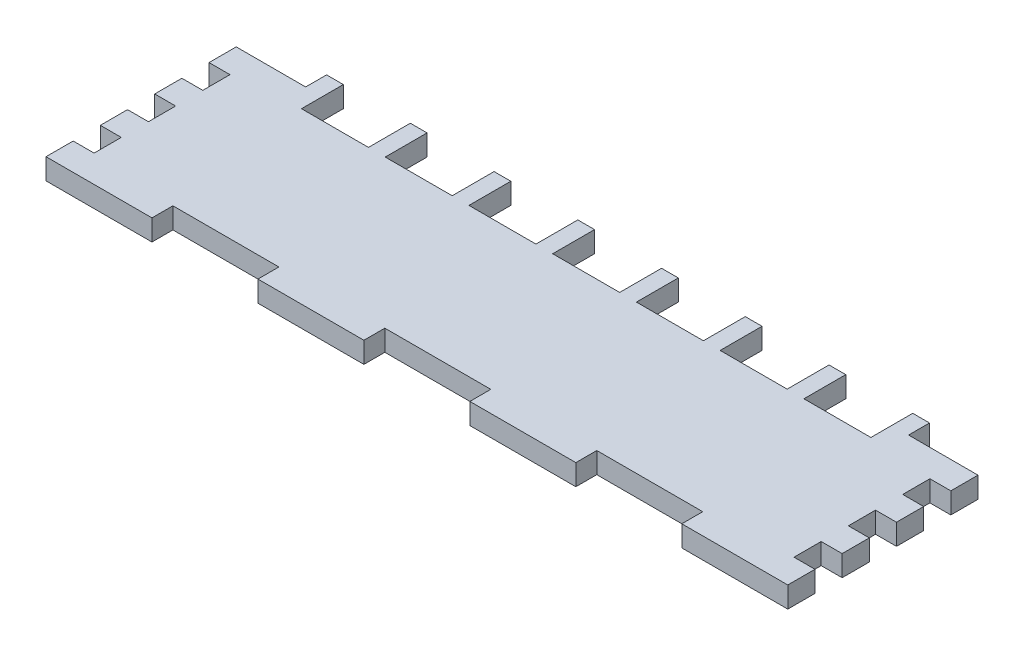
SolidWorks part; units mm, degrees
ref_plane "Front Plane" through (0, 0, 0) normal (0, 0, 1) x (1, 0, 0)
ref_plane "Top Plane" through (0, 0, 0) normal (0, 1, 0) x (1, 0, 0)
ref_plane "Right Plane" through (0, 0, 0) normal (1, 0, 0) x (0, 0, -1)
sketch "Sketch1" plane through (0, 0, 0) normal (0, 1, 0) x (1, 0, 0)
  line L48 (32.1429, 0) -> (32.1429, 6.35)
  line L49 (0, 0) -> (32.1429, 0)
  line L50 (0, 0) -> (0, 6.35)
  line L51 (0, 6.35) -> (32.1429, 6.35)
  line L52 (32.1429, 0) -> (32.1429, 6.35)
  line L53 (0, 0) -> (6.35, 0)
  line L54 (0, 0) -> (0, 8.2429)
  line L55 (0, 8.2429) -> (6.35, 8.2429)
  line L56 (6.35, 0) -> (6.35, 8.2429)
  line L57 (32.1429, 0) -> (64.2857, 0)
  line L58 (64.2857, 0) -> (64.2857, 6.35)
  line L59 (32.1429, 6.35) -> (64.2857, 6.35)
  line L60 (64.2857, 0) -> (64.2857, 6.35)
  line L61 (64.2857, 0) -> (96.4286, 0)
  line L62 (96.4286, 0) -> (96.4286, 6.35)
  line L63 (64.2857, 6.35) -> (96.4286, 6.35)
  line L64 (96.4286, 0) -> (96.4286, 6.35)
  line L65 (96.4286, 0) -> (128.5714, 0)
  line L66 (128.5714, 0) -> (128.5714, 6.35)
  line L67 (96.4286, 6.35) -> (128.5714, 6.35)
  line L72 (128.5714, 0) -> (128.5714, 6.35)
  line L73 (128.5714, 0) -> (160.7143, 0)
  line L74 (160.7143, 0) -> (160.7143, 6.35)
  line L75 (128.5714, 6.35) -> (160.7143, 6.35)
  line L76 (160.7143, 0) -> (160.7143, 6.35)
  line L77 (160.7143, 0) -> (192.8571, 0)
  line L78 (192.8571, 0) -> (192.8571, 6.35)
  line L79 (160.7143, 6.35) -> (192.8571, 6.35)
  line L80 (192.8571, 0) -> (192.8571, 6.35)
  line L81 (192.8571, 0) -> (225, 0)
  line L82 (225, 0) -> (225, 6.35)
  line L83 (192.8571, 6.35) -> (225, 6.35)
  line L84 (0, 8.2429) -> (0, 16.4857)
  line L85 (0, 8.2429) -> (6.35, 8.2429)
  line L86 (6.35, 8.2429) -> (6.35, 16.4857)
  line L87 (0, 16.4857) -> (6.35, 16.4857)
  line L88 (0, 16.4857) -> (0, 24.7286)
  line L89 (0, 16.4857) -> (6.35, 16.4857)
  line L90 (6.35, 16.4857) -> (6.35, 24.7286)
  line L91 (0, 24.7286) -> (6.35, 24.7286)
  line L98 (0, 24.7286) -> (0, 32.9714)
  line L99 (0, 24.7286) -> (6.35, 24.7286)
  line L100 (6.35, 24.7286) -> (6.35, 32.9714)
  line L101 (0, 32.9714) -> (6.35, 32.9714)
  line L102 (0, 32.9714) -> (0, 41.2143)
  line L103 (0, 32.9714) -> (6.35, 32.9714)
  line L104 (6.35, 32.9714) -> (6.35, 41.2143)
  line L105 (0, 41.2143) -> (6.35, 41.2143)
  line L106 (0, 41.2143) -> (0, 49.4571)
  line L107 (0, 41.2143) -> (6.35, 41.2143)
  line L108 (6.35, 41.2143) -> (6.35, 49.4571)
  line L109 (0, 49.4571) -> (6.35, 49.4571)
  line L110 (0, 49.4571) -> (0, 57.7)
  line L111 (0, 49.4571) -> (6.35, 49.4571)
  line L112 (6.35, 49.4571) -> (6.35, 57.7)
  line L113 (0, 57.7) -> (6.35, 57.7)
  line L114 (112.5, 0) -> (112.5, 671.069) construction
  line L115 (-187.856, 28.85) -> (254.8092, 28.85) construction
  line L116 (225, 8.2429) -> (218.65, 8.2429)
  line L117 (218.65, 0) -> (218.65, 8.2429)
  line L118 (225, 0) -> (218.65, 0)
  line L119 (225, 0) -> (225, 8.2429)
  line L120 (225, 49.4571) -> (218.65, 49.4571)
  line L121 (218.65, 49.4571) -> (218.65, 57.7)
  line L122 (225, 57.7) -> (218.65, 57.7)
  line L123 (225, 49.4571) -> (225, 57.7)
  line L124 (225, 41.2143) -> (218.65, 41.2143)
  line L125 (218.65, 41.2143) -> (218.65, 49.4571)
  line L126 (225, 49.4571) -> (218.65, 49.4571)
  line L127 (225, 41.2143) -> (225, 49.4571)
  line L128 (225, 8.2429) -> (218.65, 8.2429)
  line L129 (218.65, 8.2429) -> (218.65, 16.4857)
  line L130 (225, 16.4857) -> (218.65, 16.4857)
  line L131 (225, 8.2429) -> (225, 16.4857)
  line L132 (225, 32.9714) -> (218.65, 32.9714)
  line L133 (218.65, 32.9714) -> (218.65, 41.2143)
  line L134 (225, 41.2143) -> (218.65, 41.2143)
  line L135 (225, 32.9714) -> (225, 41.2143)
  line L136 (225, 24.7286) -> (218.65, 24.7286)
  line L137 (218.65, 24.7286) -> (218.65, 32.9714)
  line L138 (225, 32.9714) -> (218.65, 32.9714)
  line L139 (225, 24.7286) -> (225, 32.9714)
  line L140 (225, 16.4857) -> (218.65, 16.4857)
  line L141 (218.65, 16.4857) -> (218.65, 24.7286)
  line L142 (225, 24.7286) -> (218.65, 24.7286)
  line L143 (225, 16.4857) -> (225, 24.7286)
  line L144 (192.8571, 57.7) -> (225, 57.7)
  line L145 (225, 57.7) -> (225, 51.35)
  line L146 (192.8571, 51.35) -> (225, 51.35)
  line L147 (192.8571, 57.7) -> (192.8571, 51.35)
  line L148 (160.7143, 57.7) -> (192.8571, 57.7)
  line L149 (192.8571, 57.7) -> (192.8571, 51.35)
  line L150 (160.7143, 51.35) -> (192.8571, 51.35)
  line L151 (160.7143, 57.7) -> (160.7143, 51.35)
  line L152 (128.5714, 57.7) -> (160.7143, 57.7)
  line L153 (160.7143, 57.7) -> (160.7143, 51.35)
  line L154 (128.5714, 51.35) -> (160.7143, 51.35)
  line L155 (128.5714, 57.7) -> (128.5714, 51.35)
  line L156 (96.4286, 57.7) -> (128.5714, 57.7)
  line L157 (128.5714, 57.7) -> (128.5714, 51.35)
  line L158 (96.4286, 51.35) -> (128.5714, 51.35)
  line L159 (96.4286, 57.7) -> (96.4286, 51.35)
  line L160 (64.2857, 57.7) -> (96.4286, 57.7)
  line L161 (96.4286, 57.7) -> (96.4286, 51.35)
  line L162 (64.2857, 51.35) -> (96.4286, 51.35)
  line L163 (64.2857, 57.7) -> (64.2857, 51.35)
  line L164 (32.1429, 57.7) -> (64.2857, 57.7)
  line L165 (64.2857, 57.7) -> (64.2857, 51.35)
  line L166 (32.1429, 51.35) -> (64.2857, 51.35)
  line L167 (32.1429, 57.7) -> (32.1429, 51.35)
  line L168 (0, 51.35) -> (32.1429, 51.35)
  line L169 (32.1429, 57.7) -> (32.1429, 51.35)
  line L170 (0, 57.7) -> (32.1429, 57.7)
  line L171 (0, 57.7) -> (0, 51.35)
  point P56 (112.5, 6.35)
  point P58 (6.35, 28.85)
  dimension "D3" = 57.7
  dimension "D4" = 225
  dimension "D5" = 6.35
  dimension "D2" = 7
  dimension "D1" = 7
extrude "Boss-Extrude1" add sketch "Sketch1" along normal blind 6.35 contours L168 L112 L108 L104 L100 L90 L86 L56 L51 L59 L63 L67 L75 L79 L83 L117 L129 L141 L137 L133 L125 L121 L146 L150 L154 L158 L162 L166 | L170 L112 L168 L167 | L160 L163 L162 L159 | L152 L155 L154 L151 | L144 L147 L146 L121 | L121 L146 L123 L122 | L110 L168 L112 L113 | L168 L110 L109 L112 | L51 L56 L55 L54 | L49 L56 L51 L50 | L56 L49 L48 L51 | L63 L58 L61 L62 | L75 L66 L73 L74 | L81 L117 L83 L78 | L117 L81 L82 L83 | L83 L119 L116 L117 | L146 L121 L120 L123 | L132 L135 L124 L133 | L130 L143 L136 L141 | L91 L88 L87 L90 | L105 L102 L101 L104
sketch "Sketch2" plane through (0, 6.35, 0) normal (0, 1, 0) x (1, 0, 0)
  line L1 (0, 57.7) -> (225, 57.7)
  line L2 (0, 57.7) -> (0, 49.4571)
  line L3 (0, 49.4571) -> (225, 49.4571)
  line L4 (225, 57.7) -> (225, 49.4571)
extrude "Boss-Extrude2" add sketch "Sketch2" against normal up to surface (6.35 mm away) up to face at (112.5, 0, -28.85)
sketch "Sketch3" plane through (0, 6.35, 0) normal (0, 1, 0) x (1, 0, 0)
  line L0 (0, 57.7) -> (225, 57.7) construction
  line L1 (21.06, 57.7) -> (26.14, 57.7)
  line L2 (21.06, 57.7) -> (21.06, 64.05)
  line L3 (21.06, 64.05) -> (26.14, 64.05)
  line L4 (26.14, 57.7) -> (26.14, 64.05)
  line L5 (46.46, 57.7) -> (46.46, 64.05)
  line L6 (46.46, 57.7) -> (51.54, 57.7)
  line L7 (51.54, 57.7) -> (51.54, 64.05)
  line L8 (46.46, 64.05) -> (51.54, 64.05)
  line L9 (71.86, 57.7) -> (71.86, 64.05)
  line L10 (71.86, 57.7) -> (76.94, 57.7)
  line L11 (76.94, 57.7) -> (76.94, 64.05)
  line L12 (71.86, 64.05) -> (76.94, 64.05)
  line L13 (97.26, 57.7) -> (97.26, 64.05)
  line L14 (97.26, 57.7) -> (102.34, 57.7)
  line L15 (102.34, 57.7) -> (102.34, 64.05)
  line L16 (97.26, 64.05) -> (102.34, 64.05)
  line L17 (122.66, 57.7) -> (122.66, 64.05)
  line L18 (122.66, 57.7) -> (127.74, 57.7)
  line L19 (127.74, 57.7) -> (127.74, 64.05)
  line L20 (122.66, 64.05) -> (127.74, 64.05)
  line L21 (148.06, 57.7) -> (148.06, 64.05)
  line L22 (148.06, 57.7) -> (153.14, 57.7)
  line L23 (153.14, 57.7) -> (153.14, 64.05)
  line L24 (148.06, 64.05) -> (153.14, 64.05)
  line L25 (173.46, 57.7) -> (173.46, 64.05)
  line L26 (173.46, 57.7) -> (178.54, 57.7)
  line L27 (178.54, 57.7) -> (178.54, 64.05)
  line L28 (173.46, 64.05) -> (178.54, 64.05)
  line L29 (198.86, 57.7) -> (198.86, 64.05)
  line L30 (198.86, 57.7) -> (203.94, 57.7)
  line L31 (203.94, 57.7) -> (203.94, 64.05)
  line L32 (198.86, 64.05) -> (203.94, 64.05)
  line L33 (112.5, 6.35) -> (112.5, 90.7817) construction
  line L35 (96.4286, 6.35) -> (128.5714, 6.35) construction
  line L36 (122.66, 64.05) -> (112.5, 64.05) construction
  line L37 (112.5, 64.05) -> (102.34, 64.05) construction
  point P7 (23.6, 64.05)
  point P35 (49, 64.05)
  point P39 (112.5, 6.35)
  dimension "D2" = 25.4
  dimension "D3" = 5.08
  dimension "D4" = 6.35
  dimension "D1" = 8
extrude "Boss-Extrude3" add sketch "Sketch3" against normal up to surface (6.35 mm away) up to face at (112.5, 0, -21.1475)
sketch "Sketch4" plane through (0, 6.35, 0) normal (0, 1, 0) x (1, 0, 0)
  line L0 (71.86, 57.7) -> (71.86, 51.35)
  line L1 (26.14, 57.7) -> (46.46, 57.7)
  line L2 (26.14, 57.7) -> (26.14, 51.35)
  line L3 (26.14, 51.35) -> (46.46, 51.35)
  line L4 (46.46, 57.7) -> (46.46, 51.35)
  line L5 (51.54, 57.7) -> (51.54, 51.35)
  line L6 (51.54, 57.7) -> (71.86, 57.7)
  line L7 (51.54, 51.35) -> (71.86, 51.35)
  line L8 (97.26, 57.7) -> (97.26, 51.35)
  line L9 (76.94, 57.7) -> (76.94, 51.35)
  line L10 (76.94, 57.7) -> (97.26, 57.7)
  line L11 (76.94, 51.35) -> (97.26, 51.35)
  line L12 (122.66, 57.7) -> (122.66, 51.35)
  line L13 (102.34, 57.7) -> (102.34, 51.35)
  line L14 (102.34, 57.7) -> (122.66, 57.7)
  line L15 (102.34, 51.35) -> (122.66, 51.35)
  line L16 (148.06, 57.7) -> (148.06, 51.35)
  line L17 (127.74, 57.7) -> (127.74, 51.35)
  line L18 (127.74, 57.7) -> (148.06, 57.7)
  line L19 (127.74, 51.35) -> (148.06, 51.35)
  line L20 (173.46, 57.7) -> (173.46, 51.35)
  line L21 (153.14, 57.7) -> (153.14, 51.35)
  line L22 (153.14, 57.7) -> (173.46, 57.7)
  line L23 (153.14, 51.35) -> (173.46, 51.35)
  line L24 (198.86, 57.7) -> (198.86, 51.35)
  line L25 (178.54, 57.7) -> (178.54, 51.35)
  line L26 (178.54, 57.7) -> (198.86, 57.7)
  line L27 (178.54, 51.35) -> (198.86, 51.35)
  line L28 (173.46, 64.05) -> (173.46, 57.7) construction
  point P5 (198.86, 57.7)
  point P6 (173.46, 57.7)
  dimension "D2" = 6.35
  dimension "D1" = 7
extrude "Cut-Extrude1" cut sketch "Sketch4" against normal up to surface (6.35 mm away) up to face at (112.5, 0, -38.8042)
